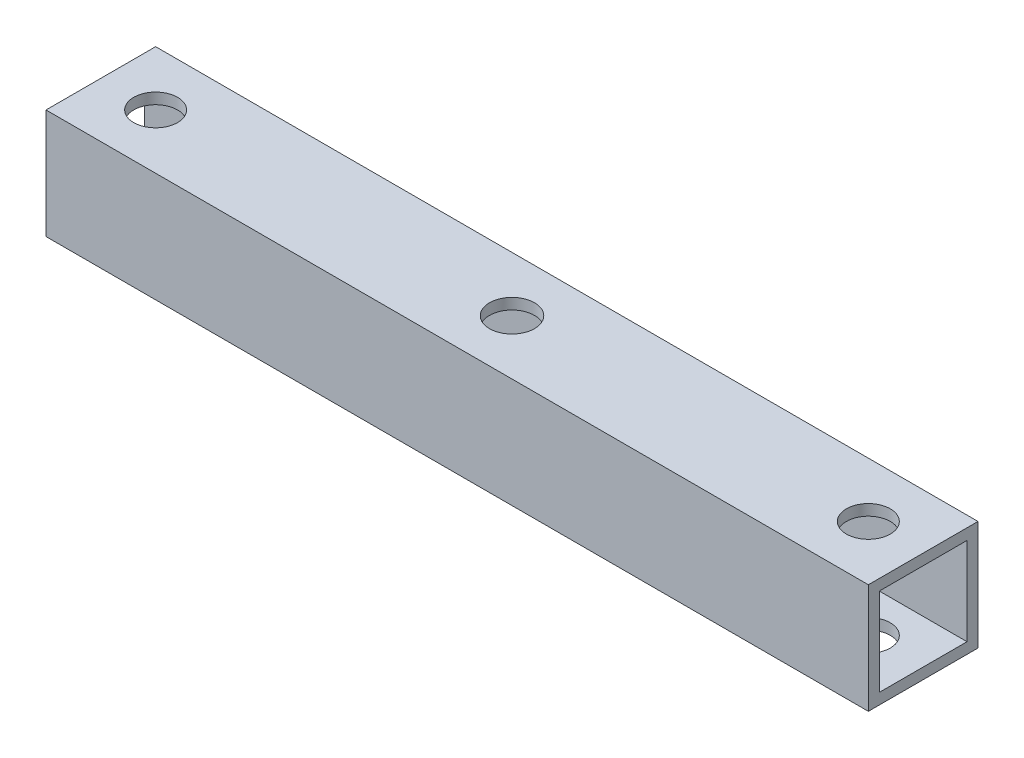
SolidWorks part; units mm, degrees
ref_plane "Front Plane" through (0, 0, 0) normal (0, 0, 1) x (1, 0, 0)
ref_plane "Top Plane" through (0, 0, 0) normal (0, 1, 0) x (1, 0, 0)
ref_plane "Right Plane" through (0, 0, 0) normal (1, 0, 0) x (0, 0, -1)
sketch "Sketch1" plane through (0, 0, 0) normal (1, 0, 0) x (0, 0, -1)
  line L0 (-8, -8) -> (-8, 8)
  line L1 (-10, -10) -> (10, -10)
  line L2 (-10, -10) -> (-10, 10)
  line L3 (-10, 10) -> (10, 10)
  line L4 (10, -10) -> (10, 10)
  line L5 (-10, -10) -> (10, 10) construction
  line L6 (-10, 10) -> (10, -10) construction
  line L7 (-8, 8) -> (8, 8)
  line L8 (8, -8) -> (8, 8)
  line L9 (-8, -8) -> (8, -8)
  point P0 (0, 0)
  dimension "D1" = 20
  dimension "D2" = 20
  dimension "D3" = 2
extrude "Boss-Extrude1" add sketch "Sketch1" along normal blind 150
sketch "Sketch2" plane through (0, 10, 0) normal (0, 1, 0) x (1, 0, 0)
  line L0 (0, 10) -> (0, -10) construction
  line L1 (150, 10) -> (150, -10) construction
  circle A0 centre (10, 0) radius 4
  circle A1 centre (140, 0) radius 4
  dimension "D1" = 8
  dimension "D2" = 8
  dimension "D3" = 10
  dimension "D4" = 10
extrude "Cut-Extrude1" cut sketch "Sketch2" against normal through all
sketch "Sketch3" plane through (0, 10, 0) normal (0, 1, 0) x (1, 0, 0)
  line L0 (0, 10) -> (0, -10) construction
  circle A0 centre (75, 0) radius 4.1
  dimension "D2" = 8.2
  dimension "D1" = 75
extrude "Cut-Extrude2" cut sketch "Sketch3" against normal through all
